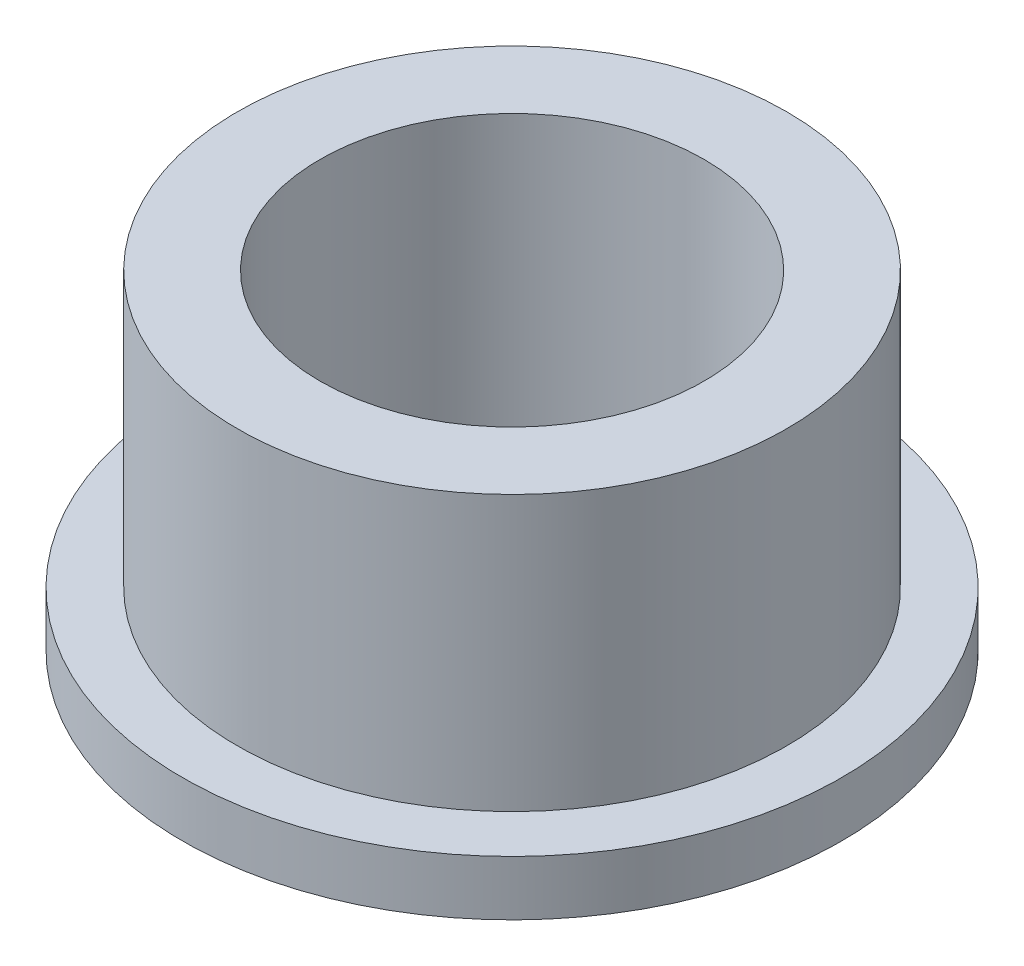
SolidWorks part; units mm, degrees
material "Commercial Bronze, UNS C22000 (90-10 Bronze)"
ref_plane "Front Plane" through (0, 0, 0) normal (0, 0, 1) x (1, 0, 0)
ref_plane "Top Plane" through (0, 0, 0) normal (0, 1, 0) x (1, 0, 0)
ref_plane "Right Plane" through (0, 0, 0) normal (1, 0, 0) x (0, 0, -1)
sketch "Sketch1" plane through (0, 0, 0) normal (0, 1, 0) x (1, 0, 0)
  circle A0 centre (0, 0) radius 11.1024
  circle A1 centre (0, 0) radius 15.875
  dimension "D1" = 31.75
extrude "Boss-Extrude1" add sketch "Sketch1" along normal blind 19.05
sketch "Sketch2" plane through (0, 0, 0) normal (0, -1, 0) x (1, 0, 0)
  circle A0 centre (0, 0) radius 19.05
  circle A1 centre (0, 0) radius 15.875
  dimension "D1" = 38.1
extrude "Boss-Extrude2" add sketch "Sketch2" against normal blind 3.175
